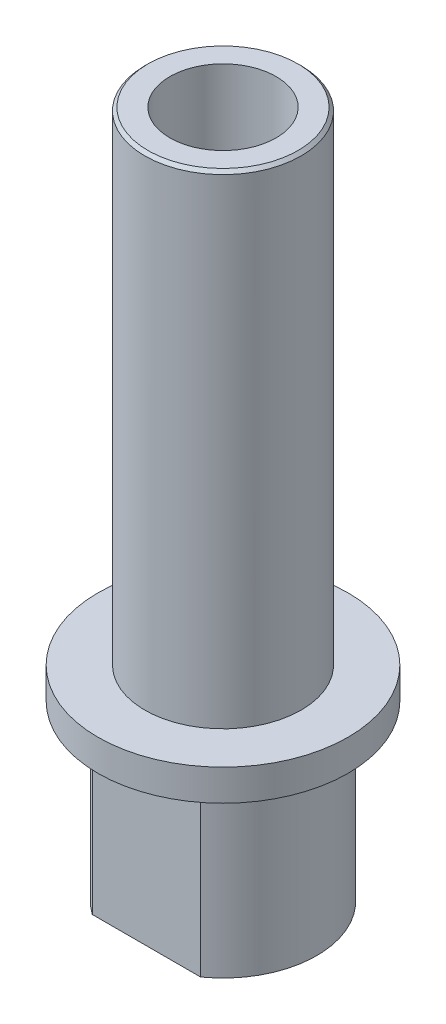
SolidWorks part; units mm, degrees
material "303"
ref_plane "前视" through (0, 0, 0) normal (0, 0, 1) x (1, 0, 0)
ref_plane "上视" through (0, 0, 0) normal (0, 1, 0) x (1, 0, 0)
ref_plane "右视" through (0, 0, 0) normal (1, 0, 0) x (0, 0, -1)
sketch "草图1" plane through (0, 0, 0) normal (0, 0, 1) x (1, 0, 0)
  line L0 (0, -1000) -> (0, 49000) construction
  line L1 (0, 0) -> (6, 0)
  line L2 (6, 0) -> (6, 11.1)
  line L3 (6, 11.1) -> (8, 11.1)
  line L4 (8, 11.1) -> (8, 13.1)
  line L5 (8, 13.1) -> (5, 13.1)
  line L6 (5, 13.1) -> (5, 44)
  line L7 (5, 44) -> (0, 44)
  line L8 (0, 44) -> (0, 0)
  dimension "D1" = 10
  dimension "D2" = 12
  dimension "D3" = 16
  dimension "D4" = 30.9
  dimension "D5" = 2
  dimension "D6" = 44
revolve "旋转1" add sketch "草图1" angle 360 about L0
sketch "草图2" plane through (0, 0, 0) normal (0, -1, 0) x (1, 0, 0)
  line L0 (0, 0) -> (10.6499, 0) construction
  line L1 (3.4627, -4.9) -> (3.4627, -6)
  line L2 (-3.4627, 4.9) -> (3.4627, 4.9)
  line L3 (-3.4627, 4.9) -> (-3.4627, 6)
  line L4 (-3.4627, 6) -> (3.4627, 6)
  line L5 (3.4627, 4.9) -> (3.4627, 6)
  line L6 (-3.4627, -6) -> (3.4627, -6)
  line L7 (-3.4627, -4.9) -> (-3.4627, -6)
  line L8 (-3.4627, -4.9) -> (3.4627, -4.9)
  circle A0 centre (0, 0) radius 6 construction
  circle A1 centre (0, 0) radius 6 construction
  dimension "D1" = 9.8
extrude "切除-拉伸1" cut sketch "草图2" against normal up to surface (11.1 mm away) up to face at (8, 11.1, 0)
hole_wizard "M8 螺纹孔1" positions "草图4" profile "草图3" tap size "M8" standard "Gb"
sketch "草图4" plane through (0, 44, 0) normal (0, 1, 0) x (1, 0, 0)
  point P0 (0, 0)
sketch "草图3" plane through (0, 44, 0) normal (1, 0, 0) x (0, 0, 1)
  line L0 (0, 0) -> (0, 21.7929)
  line L1 (0, 21.7929) -> (3.4, 19.75)
  line L2 (3.4, 19.75) -> (3.4, 0)
  line L5 (3.4, 0) -> (0, 0)
  line L10 (0, 21.7929) -> (-3.4, 19.75) construction
  line L11 (0, -6.35) -> (0, 107.95) construction
  dimension "螺纹孔钻头直径" = 6.8
  dimension "螺纹孔钻头深度" = 19.75
  dimension "导头角度" = 118
cosmetic thread "孔螺蚊线1" parameters "D1"=16, "D2"=8
hole_wizard "M8 螺纹孔2" positions "草图6" profile "草图5" tap size "M8" standard "Gb"
sketch "草图6" plane through (0, 0, 0) normal (0, -1, 0) x (-1, 0, 0)
  point P0 (0, 0)
sketch "草图5" plane through (0, 0, 0) normal (1, 0, 0) x (0, 0, -1)
  line L0 (0, 0) -> (0, 21.7929)
  line L1 (0, 21.7929) -> (3.4, 19.75)
  line L2 (3.4, 19.75) -> (3.4, 0)
  line L5 (3.4, 0) -> (0, 0)
  line L10 (0, 21.7929) -> (-3.4, 19.75) construction
  line L11 (0, -6.35) -> (0, 107.95) construction
  dimension "螺纹孔钻头直径" = 6.8
  dimension "螺纹孔钻头深度" = 19.75
  dimension "导头角度" = 118
cosmetic thread "孔螺蚊线2" parameters "D1"=16, "D2"=8
chamfer "倒角1" distance 0.2 angle 45 1 edges at (5, 44, 0)
